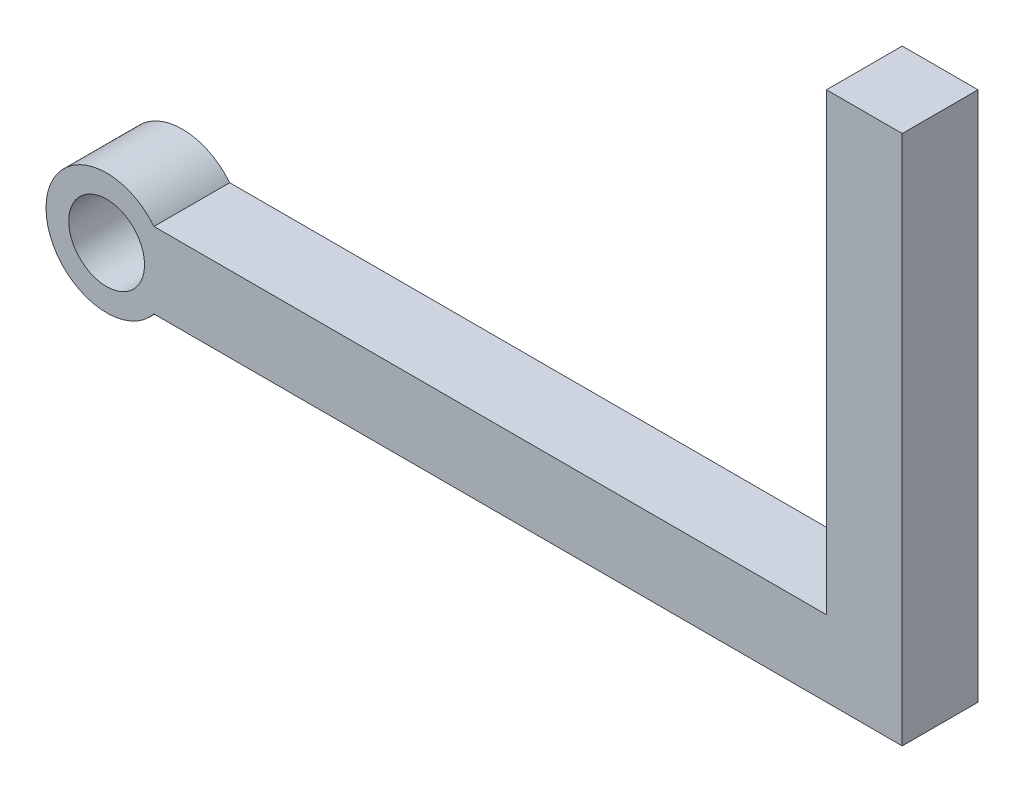
SolidWorks part; units mm, degrees
ref_plane "Front Plane" through (0, 0, 0) normal (0, 0, 1) x (1, 0, 0)
ref_plane "Top Plane" through (0, 0, 0) normal (0, 1, 0) x (1, 0, 0)
ref_plane "Right Plane" through (0, 0, 0) normal (1, 0, 0) x (0, 0, -1)
sketch "Sketch1" plane through (0, 0, 0) normal (0, 1, 0) x (1, 0, 0)
  line L5 (-63.5, 44.45) -> (-63.5, 31.75) construction
  line L6 (-63.5, -44.45) -> (63.5, -44.45)
  line L11 (-63.5, -44.45) -> (-63.5, 44.45)
  line L12 (-63.5, 44.45) -> (63.5, 44.45)
  line L13 (63.5, -44.45) -> (63.5, 44.45)
  line L14 (-63.5, -44.45) -> (63.5, 44.45) construction
  line L16 (-63.5, 44.45) -> (63.5, -44.45) construction
  line L18 (-63.5, 31.75) -> (63.5, 31.75)
  line L19 (-63.5, 31.75) -> (-63.5, 44.45)
  line L20 (-63.5, 44.45) -> (63.5, 44.45)
  line L34 (63.5, 31.75) -> (63.5, 44.45)
  line L35 (-63.5, 31.75) -> (63.5, 44.45) construction
  line L36 (-63.5, 44.45) -> (63.5, 31.75) construction
  point P0 (0, 0)
  point P12 (0, 38.1)
  dimension "D1" = 88.9
  dimension "D2" = 127
  dimension "D3" = 12.7
extrude "Boss-Extrude1" add sketch "Sketch1" along normal blind 12.7 contours L11 L18 L13 L12
sketch "Sketch9" plane through (0, 12.7, 0) normal (0, 1, 0) x (1, 0, 0)
  line L0 (63.5, 38.1) -> (57.15, 38.1) construction
  line L1 (63.5, 31.75) -> (63.5, 44.45) construction
  line L4 (50.8, 31.75) -> (63.5, 31.75)
  line L5 (50.8, 31.75) -> (50.8, 44.45)
  line L6 (50.8, 44.45) -> (63.5, 44.45)
  line L7 (63.5, 31.75) -> (63.5, 44.45)
  line L8 (50.8, 31.75) -> (63.5, 44.45) construction
  line L9 (50.8, 44.45) -> (63.5, 31.75) construction
  dimension "D1" = 6.35
extrude "Boss-Extrude2" add sketch "Sketch9" along normal blind 76.2
ref_plane "Plane5" through (0, 0, -44.45) normal (0, 0, -1) x (-1, 0, 0)
sketch "Sketch10" plane through (0, 0, -44.45) normal (0, 0, -1) x (-1, 0, 0)
  line L0 (63.5, 0) -> (69.85, 0)
  line L1 (69.85, 0) -> (69.85, 6.35)
  circle A0 centre (69.85, 6.35) radius 10.16
  dimension "D2" = 6.35
  dimension "D3" = 20.32
  dimension "D1" = 6.35
extrude "Boss-Extrude3" add sketch "Sketch10" against normal blind 12.7
hole_wizard "1/2 (0.5) Diameter Hole1" positions "3DSketch3" profile "Sketch13" hole size "1/2" standard "ANSI Inch" end condition through all
sketch3d "3DSketch3"
  line L0 (-80.01, 6.35, -44.45) -> (-69.85, 6.35, -44.45) construction
  line L2 (-69.85, 6.35, -31.75) -> (-69.85, 6.35, -44.45) construction
  arc A1 (-61.9189, 0, -44.45) -> (-61.9189, 12.7, -44.45) centre (-69.85, 6.35, -44.45) ccw construction
  point P2 (-69.85, 6.35, -44.45)
  point P12 (-69.85, 6.35, -54.61)
  dimension "D1" = 10.16
sketch "Sketch13" plane through (-69.85, 6.35, -44.45) normal (1, 0, 0) x (0, 1, 0)
  line L0 (0, 0) -> (0, 12.7)
  line L1 (0, 12.7) -> (6.35, 12.7)
  line L2 (6.35, 12.7) -> (6.35, 0)
  line L5 (6.35, 0) -> (0, 0)
  line L11 (0, -6.35) -> (0, 107.95) construction
  dimension "Thru Hole Dia." = 12.7
  dimension "Thru Hole Depth" = 12.7
